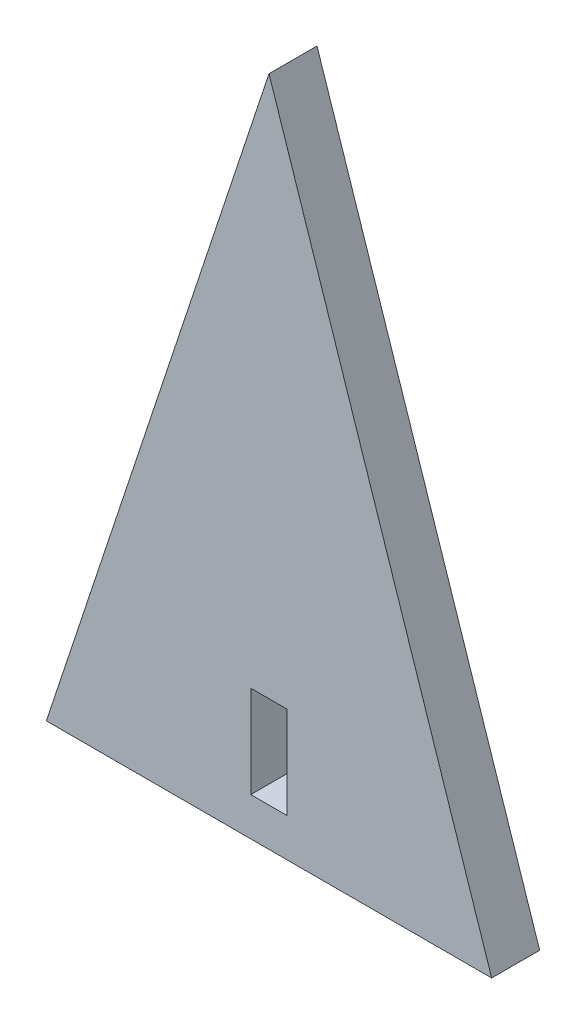
SolidWorks part; units mm, degrees
ref_plane "Front Plane" through (0, 0, 0) normal (0, 0, 1) x (1, 0, 0)
ref_plane "Top Plane" through (0, 0, 0) normal (0, 1, 0) x (1, 0, 0)
ref_plane "Right Plane" through (0, 0, 0) normal (1, 0, 0) x (0, 0, -1)
sketch "Sketch2" plane through (0, 0, 0) normal (0, 0, 1) x (1, 0, 0)
  line L0 (-16.0846, -40.3688) -> (-1.3526, 4.0812)
  line L1 (-16.0846, -40.3688) -> (13.3794, -40.3688)
  line L5 (-16.0846, -40.3688) -> (8.9252, 22.4002) construction
  line L6 (-16.0846, 48.5312) -> (13.3794, -40.3688) construction
  line L7 (-1.3526, 4.0812) -> (13.3794, -40.3688)
  line L8 (-1.3526, -40.3688) -> (-1.3526, -37.8288) construction
  line L10 (-2.5591, -37.8288) -> (-0.1461, -37.8288)
  line L11 (-2.5591, -37.8288) -> (-2.5591, -31.7328)
  line L12 (-2.5591, -31.7328) -> (-0.1461, -31.7328)
  line L13 (-0.1461, -37.8288) -> (-0.1461, -31.7328)
  point P0 (0, 0)
  point P13 (-1.3526, -37.8288)
  dimension "D1" = 29.464
  dimension "D2" = 44.45
  dimension "D3" = 2.54
  dimension "D4" = 41.91
  dimension "D5" = 2.413
  dimension "D6" = 6.096
  dimension "D7" = 5.5344
  dimension "D8" = 2.54
extrude "Boss-Extrude1" add sketch "Sketch2" along normal blind 3.175
